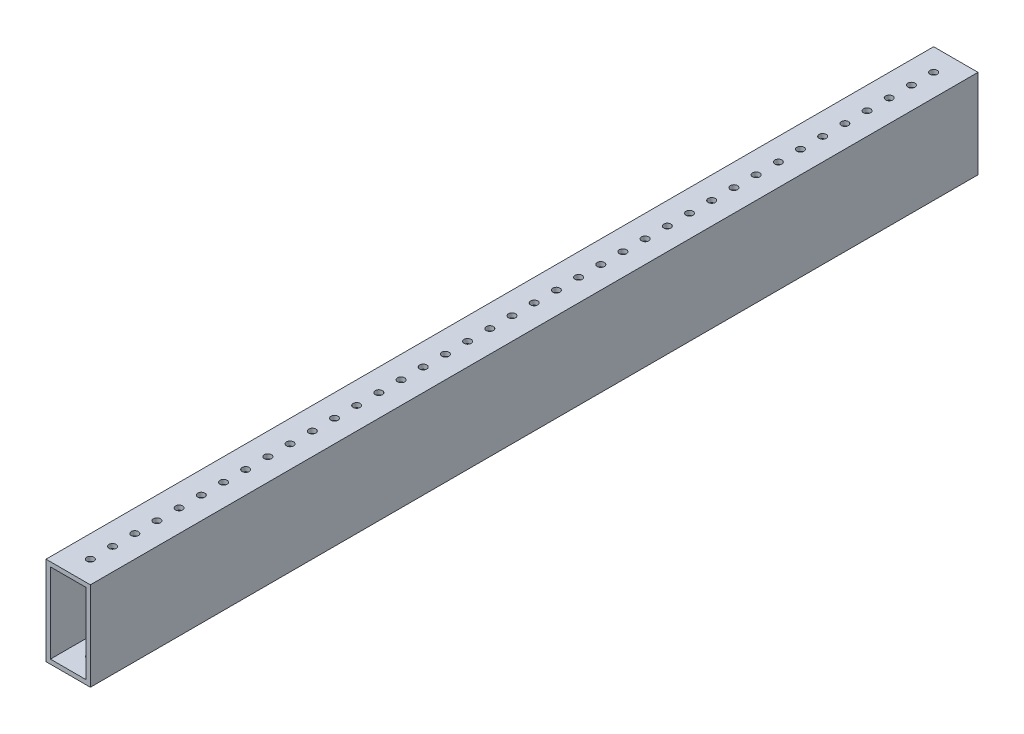
SolidWorks part; units mm, degrees
ref_plane "Front Plane" through (0, 0, 0) normal (0, 0, 1) x (1, 0, 0)
ref_plane "Top Plane" through (0, 0, 0) normal (0, 1, 0) x (1, 0, 0)
ref_plane "Right Plane" through (0, 0, 0) normal (1, 0, 0) x (0, 0, -1)
sketch "Sketch1" plane through (0, 0, 0) normal (0, 0, 1) x (1, 0, 0)
  line L0 (2.54, 2.54) -> (2.54, 48.26)
  line L1 (0, 0) -> (25.4, 0)
  line L2 (0, 0) -> (0, 50.8)
  line L3 (0, 50.8) -> (25.4, 50.8)
  line L4 (25.4, 0) -> (25.4, 50.8)
  line L5 (2.54, 48.26) -> (22.86, 48.26)
  line L6 (22.86, 2.54) -> (22.86, 48.26)
  line L7 (2.54, 2.54) -> (22.86, 2.54)
  dimension "D1" = 50.8
  dimension "D2" = 25.4
  dimension "D3" = 2.54
extrude "Boss-Extrude1" add sketch "Sketch1" along normal blind 508
sketch "Sketch2" plane through (0, 50.8, 0) normal (0, 1, 0) x (1, 0, 0)
  line L0 (0, -508) -> (0, 0) construction
  line L1 (25.4, 0) -> (0, 0) construction
  circle A0 centre (12.7, -12.7) radius 2.032
  circle A1 centre (12.7, -25.4) radius 2.032
  circle A2 centre (12.7, -38.1) radius 2.032
  circle A3 centre (12.7, -50.8) radius 2.032
  circle A4 centre (12.7, -63.5) radius 2.032
  circle A5 centre (12.7, -76.2) radius 2.032
  circle A6 centre (12.7, -88.9) radius 2.032
  circle A7 centre (12.7, -101.6) radius 2.032
  circle A8 centre (12.7, -114.3) radius 2.032
  circle A9 centre (12.7, -127) radius 2.032
  circle A10 centre (12.7, -139.7) radius 2.032
  circle A11 centre (12.7, -152.4) radius 2.032
  circle A12 centre (12.7, -165.1) radius 2.032
  circle A13 centre (12.7, -177.8) radius 2.032
  circle A14 centre (12.7, -190.5) radius 2.032
  circle A15 centre (12.7, -203.2) radius 2.032
  circle A16 centre (12.7, -215.9) radius 2.032
  circle A17 centre (12.7, -228.6) radius 2.032
  circle A18 centre (12.7, -241.3) radius 2.032
  circle A19 centre (12.7, -254) radius 2.032
  circle A20 centre (12.7, -266.7) radius 2.032
  circle A21 centre (12.7, -279.4) radius 2.032
  circle A22 centre (12.7, -292.1) radius 2.032
  circle A23 centre (12.7, -304.8) radius 2.032
  circle A24 centre (12.7, -317.5) radius 2.032
  circle A25 centre (12.7, -330.2) radius 2.032
  circle A26 centre (12.7, -342.9) radius 2.032
  circle A27 centre (12.7, -355.6) radius 2.032
  circle A28 centre (12.7, -368.3) radius 2.032
  circle A29 centre (12.7, -381) radius 2.032
  circle A30 centre (12.7, -393.7) radius 2.032
  circle A31 centre (12.7, -406.4) radius 2.032
  circle A32 centre (12.7, -419.1) radius 2.032
  circle A33 centre (12.7, -431.8) radius 2.032
  circle A34 centre (12.7, -444.5) radius 2.032
  circle A35 centre (12.7, -457.2) radius 2.032
  circle A36 centre (12.7, -469.9) radius 2.032
  circle A37 centre (12.7, -482.6) radius 2.032
  circle A38 centre (12.7, -495.3) radius 2.032
  dimension "D1" = 4.064
  dimension "D2" = 12.7
  dimension "D3" = 12.7
  dimension "D5" = 12.7
  dimension "D4" = 39
extrude "Cut-Extrude1" cut sketch "Sketch2" against normal blind 508
